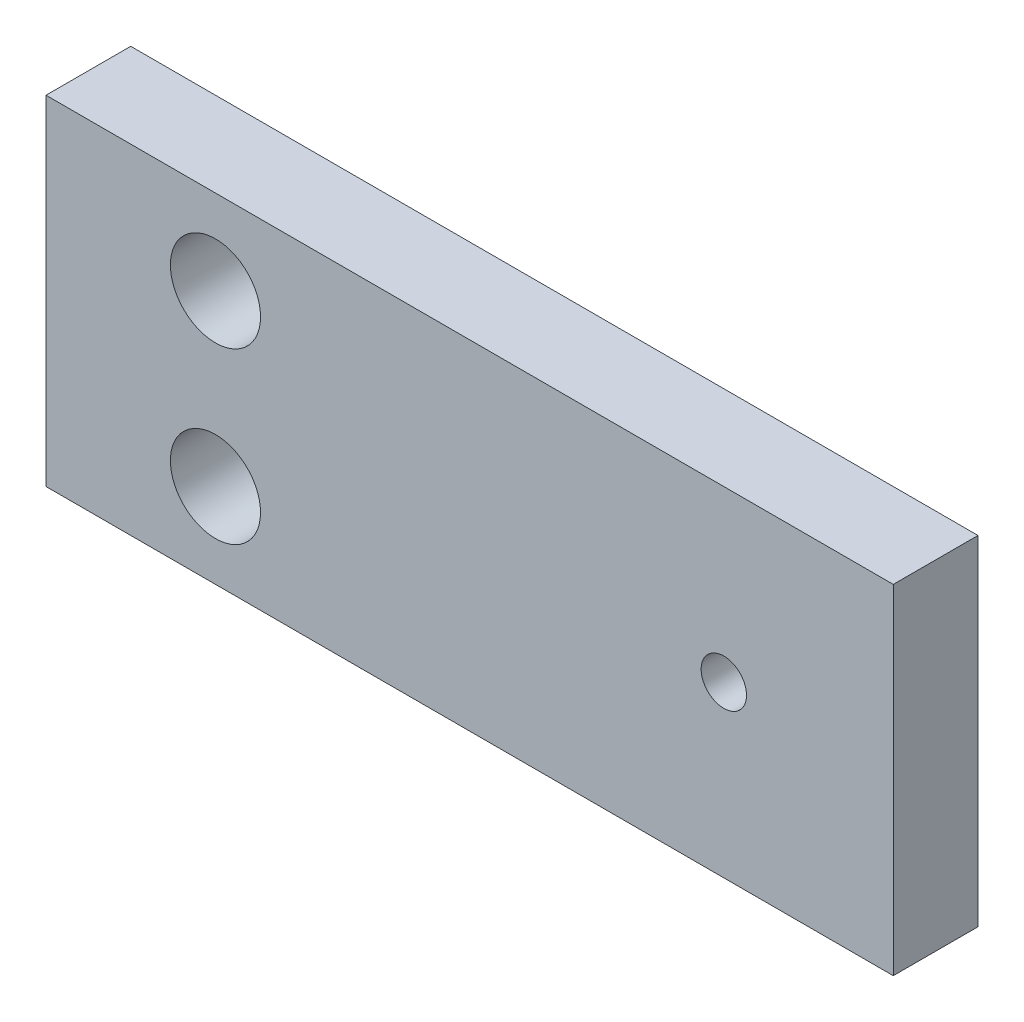
SolidWorks part; units mm, degrees
ref_plane "Front Plane" through (0, 0, 0) normal (0, 0, 1) x (1, 0, 0)
ref_plane "Top Plane" through (0, 0, 0) normal (0, 1, 0) x (1, 0, 0)
ref_plane "Right Plane" through (0, 0, 0) normal (1, 0, 0) x (0, 0, -1)
sketch "Sketch1" plane through (0, 0, 0) normal (0, 0, 1) x (1, 0, 0)
  line L1 (0, 0) -> (63.5, 0)
  line L2 (0, 0) -> (0, 25.4)
  line L3 (0, 25.4) -> (63.5, 25.4)
  line L4 (63.5, 0) -> (63.5, 25.4)
  dimension "D1" = 25.4
  dimension "D2" = 63.5
extrude "Boss-Extrude1" add sketch "Sketch1" along normal blind 6.35
sketch "Sketch2" plane through (0, 0, 6.35) normal (0, 0, 1) x (1, 0, 0)
  line L0 (12.7, 25.4) -> (12.7, 0) construction
  line L1 (63.5, 25.4) -> (0, 25.4) construction
  line L2 (0, 0) -> (63.5, 0) construction
  line L3 (0, 25.4) -> (0, 0) construction
  point P8 (12.7, 19.05)
  point P9 (12.7, 6.35)
  dimension "D1" = 12.7
  dimension "D2" = 6.35
  dimension "D3" = 6.35
hole_wizard "1/4 Clearance Hole1" positions "Sketch2" profile "Sketch3" hole size "1/4" standard "ANSI Inch" end condition through all
sketch "Sketch3" plane through (12.7, 6.35, 6.35) normal (1, 0, 0) x (0, -1, 0)
  line L0 (0, 0) -> (0, 6.35)
  line L1 (0, 6.35) -> (3.3782, 6.35)
  line L2 (3.3782, 6.35) -> (3.3782, 0)
  line L5 (3.3782, 0) -> (0, 0)
  line L11 (0, -6.35) -> (0, 107.95) construction
  dimension "Thru Hole Dia." = 6.7564
  dimension "Thru Hole Depth" = 6.35
sketch "Sketch4" plane through (0, 0, 6.35) normal (0, 0, 1) x (1, 0, 0)
  line L0 (63.5, 12.7) -> (50.8, 12.7) construction
  line L1 (63.5, 0) -> (63.5, 25.4) construction
  point P1 (50.8, 12.7)
  dimension "D1" = 12.7
hole_wizard "M3 Clearance Hole1" positions "Sketch4" profile "Sketch5" hole size "M3" standard "ANSI Metric" end condition through all
sketch "Sketch5" plane through (50.8, 12.7, 6.35) normal (1, 0, 0) x (0, -1, 0)
  line L0 (0, 0) -> (0, 6.35)
  line L1 (0, 6.35) -> (1.7, 6.35)
  line L2 (1.7, 6.35) -> (1.7, 0)
  line L5 (1.7, 0) -> (0, 0)
  line L11 (0, -6.35) -> (0, 107.95) construction
  dimension "Thru Hole Dia." = 3.4
  dimension "Thru Hole Depth" = 6.35
